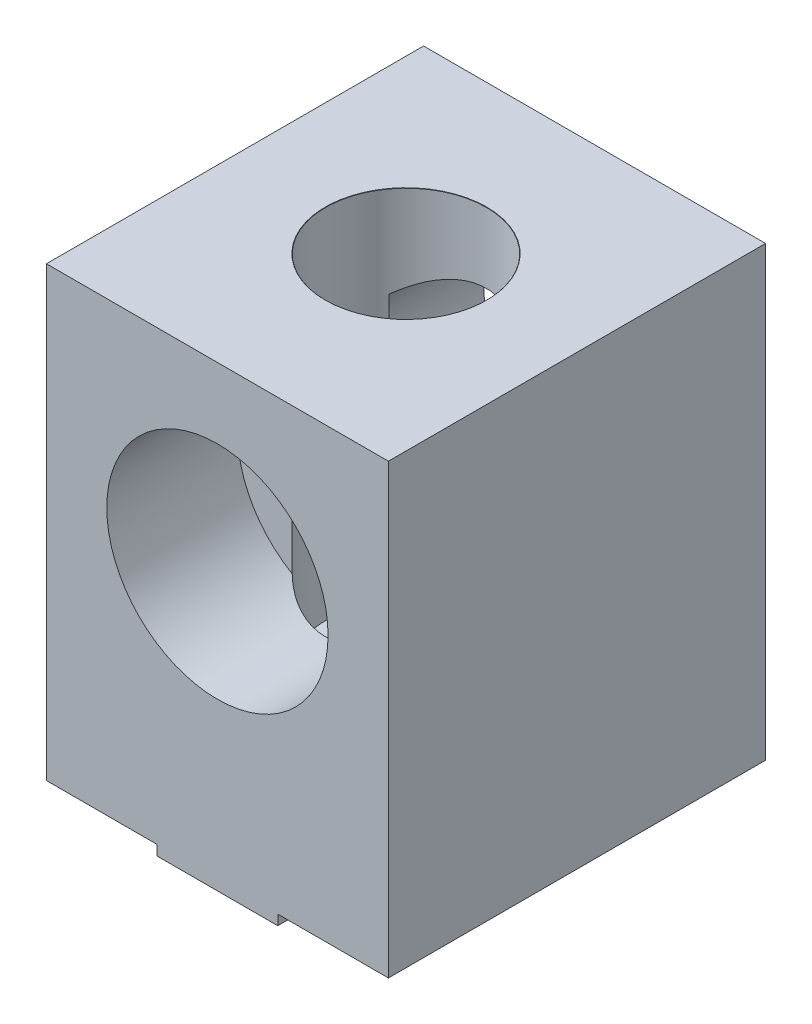
SolidWorks part; units mm, degrees
material "3.1355 (EN-AW 2024)"
ref_plane "Front" through (0, 0, 0) normal (0, 0, 1) x (1, 0, 0)
ref_plane "Top" through (0, 0, 0) normal (0, 1, 0) x (1, 0, 0)
ref_plane "Right" through (0, 0, 0) normal (1, 0, 0) x (0, 0, -1)
sketch "Эскиз1" plane through (0, 0, 0) normal (0, 1, 0) x (1, 0, 0)
  line L1 (-17, 18.75) -> (17, 18.75)
  line L2 (-17, 18.75) -> (-17, -18.75)
  line L3 (-17, -18.75) -> (17, -18.75)
  line L4 (17, 18.75) -> (17, -18.75)
  line L5 (-17, 18.75) -> (17, -18.75) construction
  line L6 (-17, -18.75) -> (17, 18.75) construction
  point P0 (0, 0)
  dimension "D1" = 34
  dimension "D2" = 37.5
extrude "База" add sketch "Эскиз1" along normal blind 44.5
sketch "Эскиз2" plane through (0, 0, 0) normal (0, -1, 0) x (1, 0, 0)
  line L0 (-17, 18.75) -> (17, 18.75) construction
  line L1 (-6, -18.75) -> (6, -18.75)
  line L2 (-6, -18.75) -> (-6, 18.75)
  line L3 (-6, 18.75) -> (6, 18.75)
  line L4 (6, -18.75) -> (6, 18.75)
  line L5 (-6, -18.75) -> (6, 18.75) construction
  line L6 (-6, 18.75) -> (6, -18.75) construction
  point P0 (0, 0)
  dimension "D1" = 12
extrude "Напрявляющая" add sketch "Эскиз2" along normal blind 1
sketch "Эскиз3" plane through (0, 0, 18.75) normal (0, 0, 1) x (1, 0, 0)
  circle A0 centre (0, 26.5) radius 6.5
  dimension "D2" = 13
  dimension "D1" = 26.5
extrude "Вырез-Вытянуть1" cut sketch "Эскиз3" against normal through all
sketch "Эскиз4" plane through (0, 0, 18.75) normal (0, 0, 1) x (1, 0, 0)
  circle A0 centre (0, 26.5) radius 11
  dimension "D1" = 22
extrude "Подшипник и сальник" cut sketch "Эскиз4" against normal blind 13
sketch "Эскиз5" plane through (0, 0, -18.75) normal (0, 0, -1) x (-1, 0, 0)
  circle A0 centre (0, 26.5) radius 11
  dimension "D1" = 22
extrude "Подшипник" cut sketch "Эскиз5" against normal blind 14
hole_wizard "К профилю M6" positions "Эскиз8" profile "Эскиз7" counterbore size "M6" standard "DIN" end condition through all
sketch "Эскиз8" plane through (0, 44.5, 0) normal (0, 1, 0) x (1, 0, 0)
  point P0 (0, 0)
sketch "Эскиз7" plane through (0, 44.5, 0) normal (1, 0, 0) x (0, 0, 1)
  line L0 (0, 0) -> (0, 45.5)
  line L1 (0, 45.5) -> (3.3, 45.5)
  line L3 (3.3, 45.5) -> (3.3, 35.6)
  line L4 (8, 35.6) -> (3.3, 35.6)
  line L5 (8, 35.6) -> (8, 0.025)
  line L6 (8, 0.025) -> (8.025, 0)
  line L7 (8.025, 0) -> (0, 0)
  line L8 (-8, 0.025) -> (-8.025, 0) construction
  line L11 (0, -6.35) -> (0, 107.95) construction
  dimension "Диаметр сквозного отверстия" = 6.6
  dimension "Глубина сквозного отверстия" = 45.5
  dimension "Диаметр цековки" = 16
  dimension "Глубина цековки" = 35.6
  dimension "Диаметр передней зенковки" = 16.05
  dimension "Угол передней зенковки" = 90
